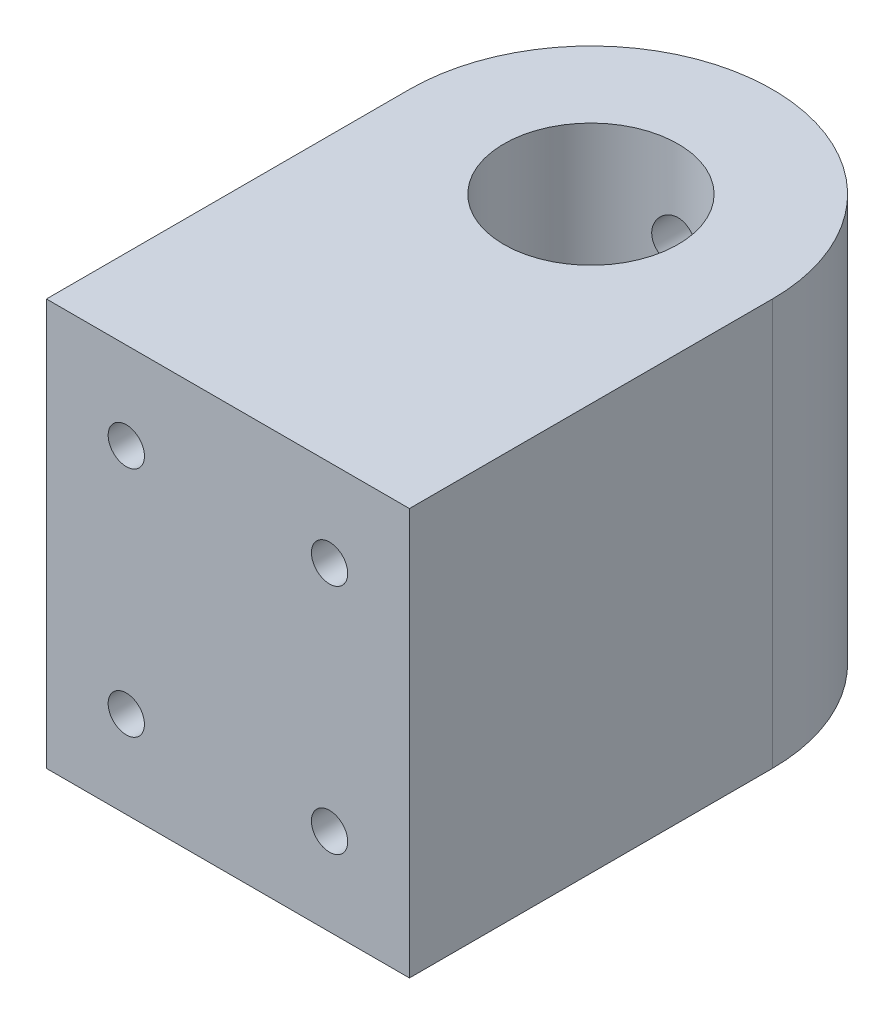
SolidWorks part; units mm, degrees
material "6061 合金"
ref_plane "前视基准面" through (0, 0, 0) normal (0, 0, 1) x (1, 0, 0)
ref_plane "上视基准面" through (0, 0, 0) normal (0, 1, 0) x (1, 0, 0)
ref_plane "右视基准面" through (0, 0, 0) normal (1, 0, 0) x (0, 0, -1)
sketch "草图1" plane through (0, 0, 0) normal (0, 1, 0) x (1, 0, 0)
  line L2 (-12.5, -25) -> (12.5, -25)
  line L3 (-12.5, -25) -> (-12.5, 0)
  line L5 (12.5, -25) -> (12.5, 0)
  arc A0 (12.5, 0) -> (-12.5, 0) centre (0, 0) ccw
  circle A1 centre (0, 0) radius 6
  point P3 (0, -12.5)
  dimension "D1" = 25
  dimension "D3" = 12
extrude "凸台-拉伸1" add sketch "草图1" along normal mid plane 28
sketch "草图7" plane through (0, 0, 0) normal (0, 0, 1) x (1, 0, 0)
  line L0 (0, 0) -> (9.3494, 0) construction
  circle A0 centre (0, -8) radius 1.6
  circle A1 centre (0, 8) radius 1.6
  dimension "D1" = 8
extrude "切除-拉伸2" cut sketch "草图7" against normal through all
hole_wizard "M3 螺纹孔1" positions "3D草图1" profile "草图8" tap size "M3" standard "GB"
sketch3d "3D草图1"
  point P0 (-7, -8, 25)
  point P7 (7, -8, 25)
  point P9 (7, 8, 25)
  point P11 (-7, 8, 25)
sketch "草图8" plane through (-7, -8, 25) normal (1, 0, 0) x (0, -1, 0)
  line L0 (0, 0) -> (0, 10.2511)
  line L1 (0, 10.2511) -> (1.25, 9.5)
  line L2 (1.25, 9.5) -> (1.25, 0)
  line L5 (1.25, 0) -> (0, 0)
  line L10 (0, 10.2511) -> (-1.25, 9.5) construction
  line L11 (0, -6.35) -> (0, 107.95) construction
  dimension "螺纹孔钻头直径" = 2.5
  dimension "螺纹孔钻头深度" = 9.5
  dimension "导头角度" = 118
cosmetic thread "孔螺蚊线1" parameters "D1"=8, "D2"=3
cosmetic thread "孔螺蚊线2" parameters "D1"=8, "D2"=3
cosmetic thread "孔螺蚊线3" parameters "D1"=8, "D2"=3
cosmetic thread "孔螺蚊线4" parameters "D1"=8, "D2"=3
